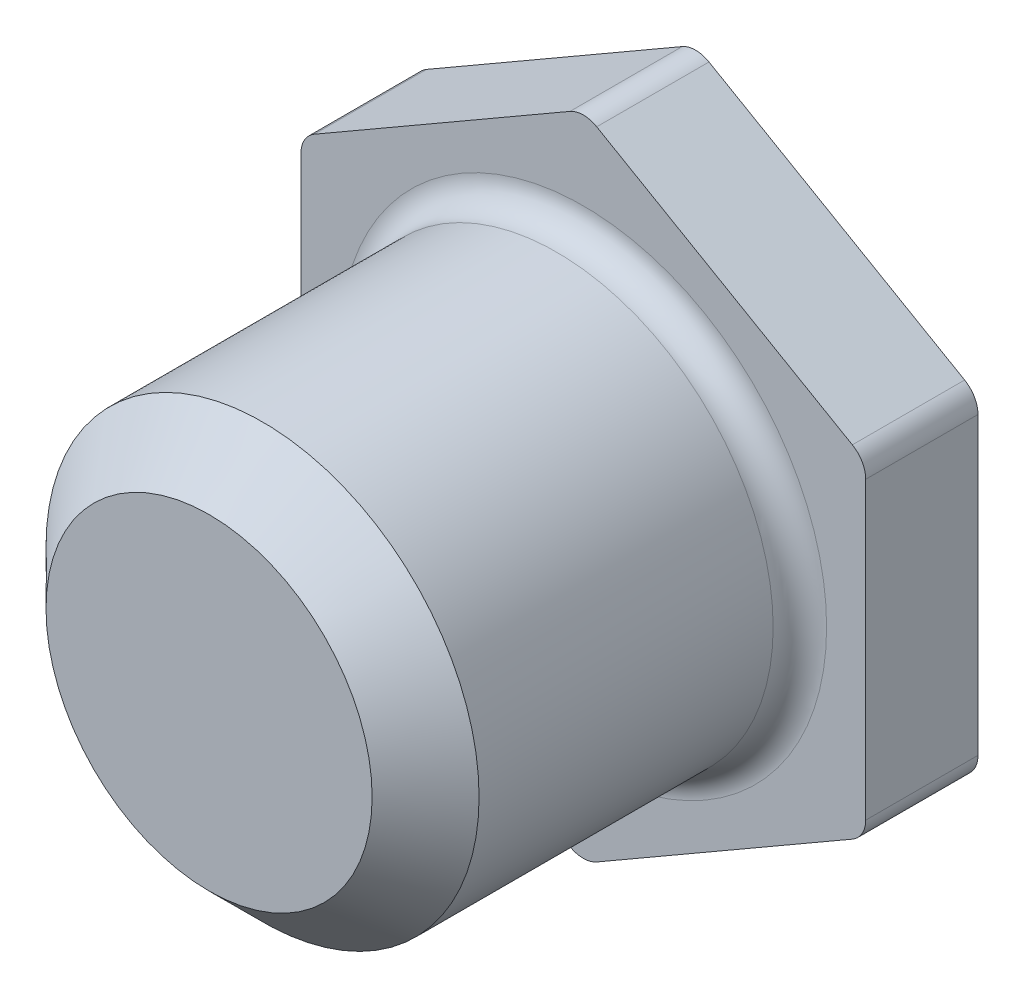
SolidWorks part; units mm, degrees
ref_plane "Front Plane" through (0, 0, 0) normal (0, 0, 1) x (1, 0, 0)
ref_plane "Top Plane" through (0, 0, 0) normal (0, 1, 0) x (1, 0, 0)
ref_plane "Right Plane" through (0, 0, 0) normal (1, 0, 0) x (0, 0, -1)
sketch "Sketch1" plane through (0, 0, 0) normal (0, 0, 1) x (1, 0, 0)
  line L0 (5.2813, 3.0492) -> (0, 6.0983)
  line L7 (0, 8.35) -> (-7.2313, 4.175)
  line L8 (-7.2313, 4.175) -> (-7.2313, -4.175)
  line L9 (-7.2313, -4.175) -> (0, -8.35)
  line L10 (0, -8.35) -> (7.2313, -4.175)
  line L11 (7.2313, -4.175) -> (7.2313, 4.175)
  line L12 (7.2313, 4.175) -> (0, 8.35)
  line L13 (0, 6.0983) -> (-5.2813, 3.0492)
  line L14 (-5.2813, 3.0492) -> (-5.2813, -3.0492)
  line L15 (-5.2813, -3.0492) -> (0, -6.0983)
  line L16 (0, -6.0983) -> (5.2813, -3.0492)
  line L17 (5.2813, -3.0492) -> (5.2813, 3.0492)
  circle A0 centre (0, 0) radius 8.35 construction
  dimension "D1" = 16.7
  dimension "D2" = 1.95
extrude "Boss-Extrude1" add sketch "Sketch1" along normal blind 2.1 contours L0 L13 L14 L15 L16 L17
sketch "Sketch2" plane through (0, 0, 2.1) normal (0, 0, 1) x (1, 0, 0)
  circle A0 centre (0, 0) radius 4.05
  dimension "D1" = 8.1
extrude "Boss-Extrude2" add sketch "Sketch2" along normal blind 7
fillet "Fillet1" radius 0.5 7 edges at (4.05, 0, 2.1) (-5.2813, 3.0492, 1.05) (-5.2813, -3.0492, 1.05) (0, -6.0983, 1.05) (5.2813, -3.0492, 1.05) (5.2813, 3.0492, 1.05) (0, 6.0983, 1.05)
chamfer "Chamfer1" distance 1 angle 45 1 edges at (4.05, 0, 9.1)
